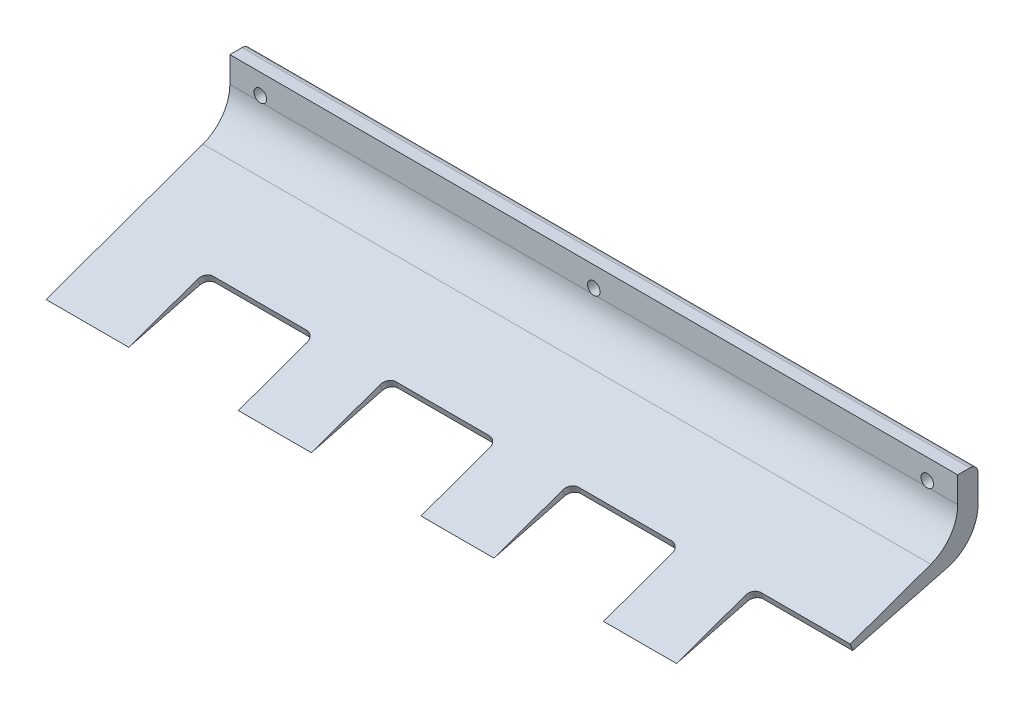
SolidWorks part; units mm, degrees
material "POLYURETHANE (11671)"
ref_plane "Front Plane" through (0, 0, 0) normal (0, 0, 1) x (1, 0, 0)
ref_plane "Top Plane" through (0, 0, 0) normal (0, 1, 0) x (1, 0, 0)
ref_plane "Right Plane" through (0, 0, 0) normal (1, 0, 0) x (0, 0, -1)
sketch "Sketch1" plane through (0, 0, 0) normal (1, 0, 0) x (0, 0, -1)
  line L0 (0, 26.1389) -> (0, 11.1389) construction
  line L1 (0, 11.1389) -> (-47.8152, -3.4796) construction
  line L2 (-2.5, 26.1389) -> (-2.5, 12.7316)
  line L3 (2.5, 26.1389) -> (2.5, 9.5463)
  line L4 (-2.5, 12.7316) -> (-47.8152, -3.4796)
  line L6 (-2.5, 26.1389) -> (2.5, 26.1389)
  line L7 (2.5, 26.1389) -> (2.5, 11.1389) construction
  line L9 (-2.5, 26.1389) -> (-2.5, 11.1389) construction
  line L11 (-47.8152, -3.4796) -> (2.5, 9.5463)
  dimension "D1" = 15
  dimension "D2" = 50
  dimension "D3" = 107
  dimension "D4" = 2.5
  dimension "D5" = 2.5
extrude "Boss-Extrude1" add sketch "Sketch1" along normal blind 179.4
fillet "Fillet1" radius 10 2 edges at (89.7, 12.7316, 2.5) (89.7, 9.5463, -2.5)
fillet "Fillet3" radius 2 1 edges at (89.7, 26.1389, -2.5)
sketch "Sketch3" plane through (0, 0, 2.5) normal (0, 0, 1) x (1, 0, 0)
  line L0 (89.7, 31.7824) -> (89.7, 20.4955) construction
  line L2 (179.4, 26.1389) -> (0, 26.1389) construction
  line L3 (0, 26.1389) -> (0, 19.7748) construction
  line L5 (0, 26.1389) -> (179.4, 26.1389) construction
  circle A0 centre (7.5, 21.1389) radius 1.55
  circle A3 centre (171.9, 21.1389) radius 1.55
  circle A4 centre (89.7, 21.1389) radius 1.55
  point P4 (89.7, 26.1389)
  point P15 (0, 0)
  dimension "D1" = 3.1
  dimension "D2" = 5
  dimension "D3" = 7.5
  dimension "D4" = 3.1
extrude "Cut-Extrude2" cut sketch "Sketch3" against normal mid plane 20
sketch "Sketch6" plane through (0, 12.08, 4.3215) normal (0, 0.9416, 0.3368) x (1, 0, 0)
  line L1 (182.4, -46.1931) -> (155.4, -46.1931)
  line L2 (182.4, -46.1931) -> (182.4, -26.1931)
  line L3 (182.4, -26.1931) -> (155.4, -26.1931)
  line L4 (155.4, -46.1931) -> (155.4, -26.1931)
  line L5 (179.4, -25.6509) -> (-17.9032, -25.6509) construction
  line L6 (179.4, -5.1086) -> (179.4, -46.1931) construction
  line L7 (137.4, -46.1931) -> (137.4, -26.1931)
  line L8 (137.4, -46.1931) -> (110.4, -46.1931)
  line L9 (110.4, -46.1931) -> (110.4, -26.1931)
  line L10 (137.4, -26.1931) -> (110.4, -26.1931)
  line L11 (92.4, -46.1931) -> (92.4, -26.1931)
  line L12 (92.4, -46.1931) -> (65.4, -46.1931)
  line L13 (65.4, -46.1931) -> (65.4, -26.1931)
  line L14 (92.4, -26.1931) -> (65.4, -26.1931)
  line L15 (47.4, -46.1931) -> (47.4, -26.1931)
  line L16 (47.4, -46.1931) -> (20.4, -46.1931)
  line L17 (20.4, -46.1931) -> (20.4, -26.1931)
  line L18 (47.4, -26.1931) -> (20.4, -26.1931)
  line L19 (179.4, -46.1931) -> (0, -46.1931) construction
  dimension "D1" = 27
  dimension "D2" = 20
  dimension "D3" = 4
  dimension "D4" = 24
extrude "Cut-Extrude4" cut sketch "Sketch6" against normal up to next
fillet "Fillet4" radius 2 7 edges at (110.4, 2.4052, 28.6792) (155.4, 2.4052, 28.6792) (137.4, 2.4052, 28.6792) (92.4, 2.4052, 28.6792) (65.4, 2.4052, 28.6792) (47.4, 2.4052, 28.6792) (20.4, 2.4052, 28.6792)
